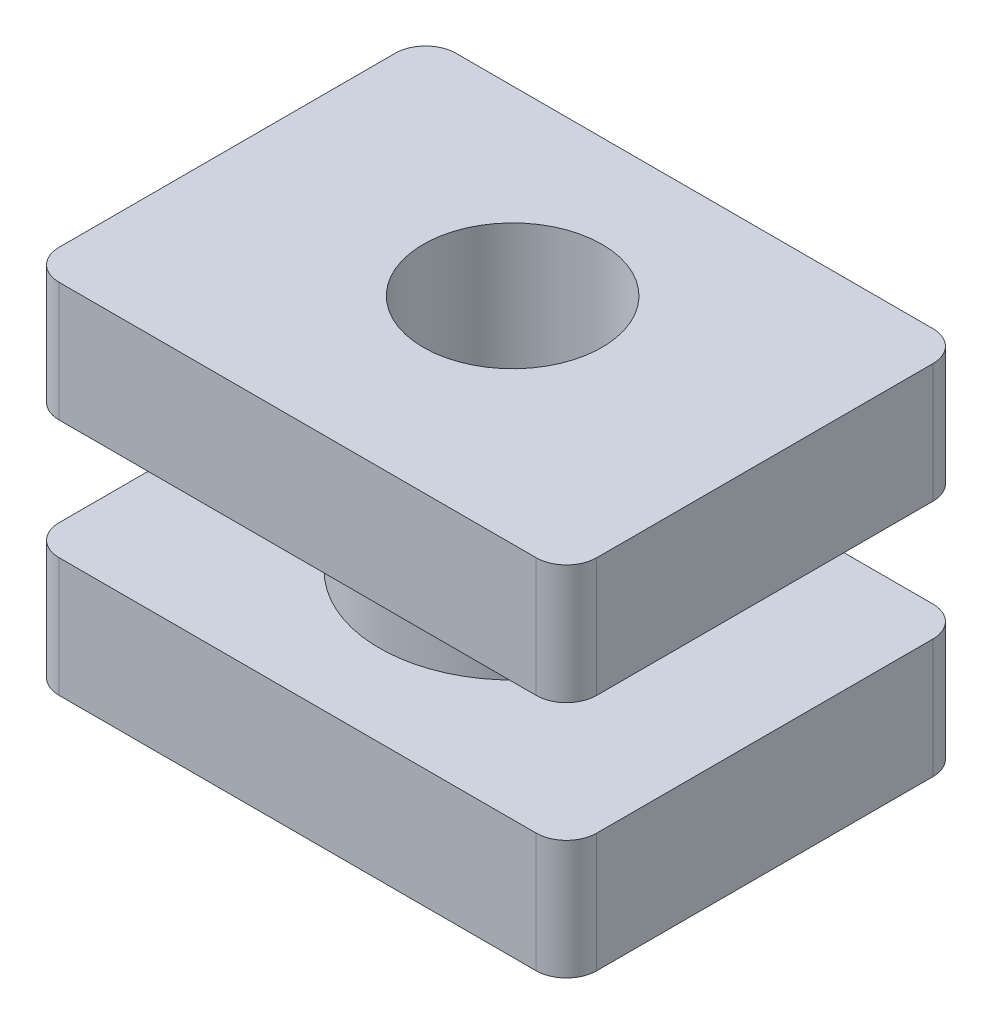
SolidWorks part; units mm, degrees
ref_plane "Front Plane" through (0, 0, 0) normal (0, 0, 1) x (1, 0, 0)
ref_plane "Top Plane" through (0, 0, 0) normal (0, 1, 0) x (1, 0, 0)
ref_plane "Right Plane" through (0, 0, 0) normal (1, 0, 0) x (0, 0, -1)
sketch "Sketch1" plane through (0, 0, 0) normal (0, 1, 0) x (1, 0, 0)
  line L0 (0, 2.4899) -> (0, -2.7943) construction
  line L1 (-4.5085, 2.54) -> (-4.5085, -3.0988)
  line L2 (4.5085, 2.54) -> (4.5085, -3.0988)
  line L3 (0, 1.4986) -> (5.0505, 1.4986) construction
  line L4 (0, -1.4986) -> (5.0505, -1.4986) construction
  line L5 (-4.0005, -3.6068) -> (4.0005, -3.6068)
  line L6 (-4.0005, 3.048) -> (4.0005, 3.048)
  line L7 (0, 3.048) -> (5.0505, 3.048) construction
  line L8 (-4.5085, 2.4899) -> (-4.5085, -2.7943) construction
  line L9 (0, -3.6068) -> (5.0505, -3.6068) construction
  line L10 (4.5085, 2.4899) -> (4.5085, -2.7943) construction
  circle A0 centre (0, 0) radius 1.4986
  arc A1 (4.0005, 3.048) -> (4.5085, 2.54) centre (4.0005, 2.54) cw
  arc A2 (4.5085, -3.0988) -> (4.0005, -3.6068) centre (4.0005, -3.0988) cw
  arc A3 (-4.0005, -3.6068) -> (-4.5085, -3.0988) centre (-4.0005, -3.0988) cw
  arc A4 (-4.5085, 2.54) -> (-4.0005, 3.048) centre (-4.0005, 2.54) cw
  dimension "D1" = 2.9972
  dimension "D6" = 0.508
  dimension "D2" = 4.5085
  dimension "D3" = 4.5085
  dimension "D4" = 2.1082
  dimension "D5" = 1.5494
extrude "Boss-Extrude1" add sketch "Sketch1" along normal blind 2
sketch "Sketch2" plane through (0, 2, 0) normal (0, 1, 0) x (1, 0, 0)
  line L0 (0, 0) -> (0, 4.0966) construction
  line L1 (1.4986, 1.6584) -> (1.4986, 3.048)
  line L2 (-1.4986, 1.6584) -> (-1.4986, 3.048)
  line L4 (4.0005, 3.048) -> (-4.0005, 3.048)
  line L5 (-4.5085, 2.54) -> (-4.5085, -3.0988)
  line L6 (-4.0005, -3.6068) -> (4.0005, -3.6068)
  line L7 (4.5085, -3.0988) -> (4.5085, 2.54)
  line L8 (1.4986, 3.048) -> (-1.4986, 3.048)
  line L12 (-1.4986, 0) -> (-1.4986, 4.0966) construction
  line L13 (1.4986, 0) -> (1.4986, 4.0966) construction
  arc A1 (-1.4986, 1.6584) -> (1.4986, 1.6584) centre (0, 0) ccw
  circle A2 centre (0, 0) radius 1.4986 construction
  circle A3 centre (0, 0) radius 1.4986
  arc A4 (4.5085, 2.54) -> (4.0005, 3.048) centre (4.0005, 2.54) ccw
  arc A5 (-4.0005, 3.048) -> (-4.5085, 2.54) centre (-4.0005, 2.54) ccw
  arc A6 (-4.5085, -3.0988) -> (-4.0005, -3.6068) centre (-4.0005, -3.0988) ccw
  arc A7 (4.0005, -3.6068) -> (4.5085, -3.0988) centre (4.0005, -3.0988) ccw
  dimension "D2" = 4.4704
  dimension "D1" = 0
  dimension "D3" = 1.4986
  dimension "D4" = 1.4986
extrude "Boss-Extrude2" add sketch "Sketch2" along normal blind 2
sketch "Sketch3" plane through (0, 4, 0) normal (0, 1, 0) x (1, 0, 0)
  line L7 (1.4986, 3.048) -> (1.4986, 1.6584)
  line L8 (-1.4986, 1.6584) -> (-1.4986, 3.048)
  line L9 (-1.4986, 3.048) -> (-4.0005, 3.048)
  line L10 (-4.5085, 2.54) -> (-4.5085, -3.0988)
  line L11 (-4.0005, -3.6068) -> (4.0005, -3.6068)
  line L12 (4.5085, -3.0988) -> (4.5085, 2.54)
  line L13 (4.0005, 3.048) -> (1.4986, 3.048)
  line L17 (-4.5085, 2.54) -> (-4.5085, -3.0988)
  line L18 (-4.0005, -3.6068) -> (4.0005, -3.6068)
  line L19 (4.5085, -3.0988) -> (4.5085, 2.54)
  line L20 (4.0005, 3.048) -> (-4.0005, 3.048)
  circle A0 centre (0, 0) radius 1.4986 construction
  circle A1 centre (0, 0) radius 1.4986
  arc A5 (-1.4986, 1.6584) -> (1.4986, 1.6584) centre (0, 0) ccw
  arc A6 (-4.0005, 3.048) -> (-4.5085, 2.54) centre (-4.0005, 2.54) ccw
  arc A7 (-4.5085, -3.0988) -> (-4.0005, -3.6068) centre (-4.0005, -3.0988) ccw
  arc A8 (4.0005, -3.6068) -> (4.5085, -3.0988) centre (4.0005, -3.0988) ccw
  arc A9 (4.5085, 2.54) -> (4.0005, 3.048) centre (4.0005, 2.54) ccw
  arc A11 (-4.0005, 3.048) -> (-4.5085, 2.54) centre (-4.0005, 2.54) ccw
  arc A12 (-4.5085, -3.0988) -> (-4.0005, -3.6068) centre (-4.0005, -3.0988) ccw
  arc A13 (4.0005, -3.6068) -> (4.5085, -3.0988) centre (4.0005, -3.0988) ccw
  arc A14 (4.5085, 2.54) -> (4.0005, 3.048) centre (4.0005, 2.54) ccw
  dimension "D1" = 0
extrude "Boss-Extrude3" add sketch "Sketch3" along normal blind 2
scale "Scale1" scale about centroid uniform scaling yes scale factor 0.6
